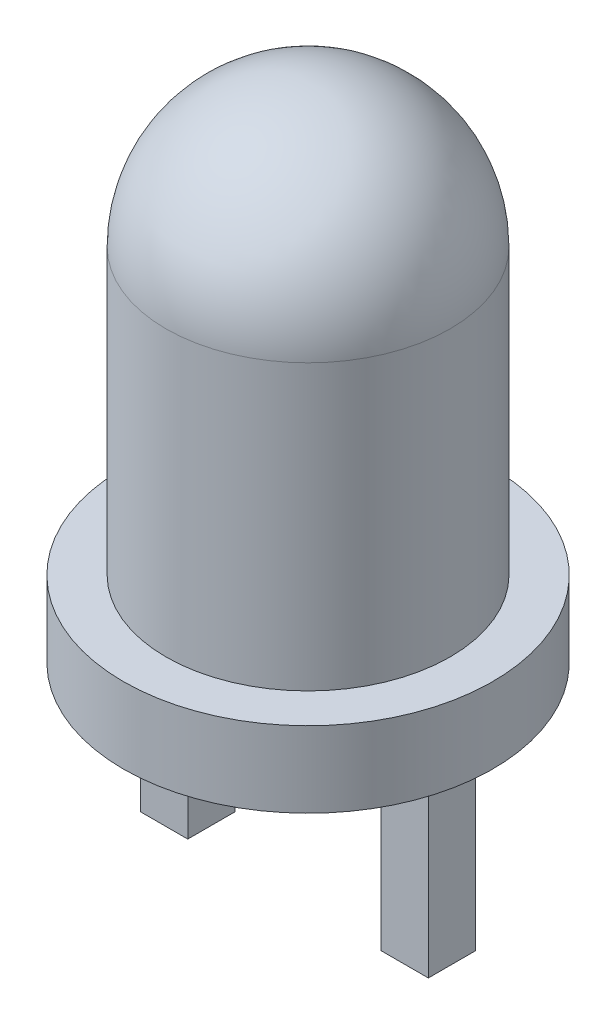
SolidWorks part; units mm, degrees
ref_plane "Front" through (0, 0, 0) normal (0, 0, 1) x (1, 0, 0)
ref_plane "Top" through (0, 0, 0) normal (0, 1, 0) x (1, 0, 0)
ref_plane "Right" through (0, 0, 0) normal (1, 0, 0) x (0, 0, -1)
sketch "Эскиз1" plane through (0, 0, 0) normal (0, 0, 1) x (1, 0, 0)
  line L0 (0, 0) -> (-1.95, 0)
  line L1 (-1.95, 0) -> (-1.95, 0.8)
  line L2 (-1.95, 0.8) -> (0, 0.8)
  line L3 (0, 0.8) -> (0, 0)
  line L4 (0, 8.7839) -> (0, -3.9548) construction
  line L5 (-1.5, 3.8) -> (-1.5, 0.8)
  line L6 (0, 5.3) -> (0, 0.8)
  arc A0 (-1.5, 3.8) -> (0, 5.3) centre (0, 3.8) cw
  dimension "D2" = 1.5
  dimension "D1" = 1.95
  dimension "D3" = 4.5
  dimension "D4" = 0.8
revolve "Повернуть1" add sketch "Эскиз1" angle 360 about L4
sketch "Эскиз2" plane through (0, 0, 0) normal (0, -1, 0) x (1, 0, 0)
  line L0 (0, 0.5791) -> (0, -1.0714) construction
  line L1 (-1.52, 0.25) -> (-1.02, 0.25)
  line L2 (-1.52, 0.25) -> (-1.52, -0.25)
  line L3 (-1.52, -0.25) -> (-1.02, -0.25)
  line L4 (-1.02, 0.25) -> (-1.02, -0.25)
  line L5 (1.02, 0.25) -> (1.02, -0.25)
  line L6 (1.52, -0.25) -> (1.02, -0.25)
  line L7 (1.52, 0.25) -> (1.52, -0.25)
  line L8 (1.52, 0.25) -> (1.02, 0.25)
  point P4 (-1.02, 0)
  point P6 (-1.27, 0.25)
  dimension "D1" = 0.5
  dimension "D2" = 0.5
  dimension "D3" = 1.27
extrude "Бобышка-Вытянуть1" add sketch "Эскиз2" along normal blind 2
